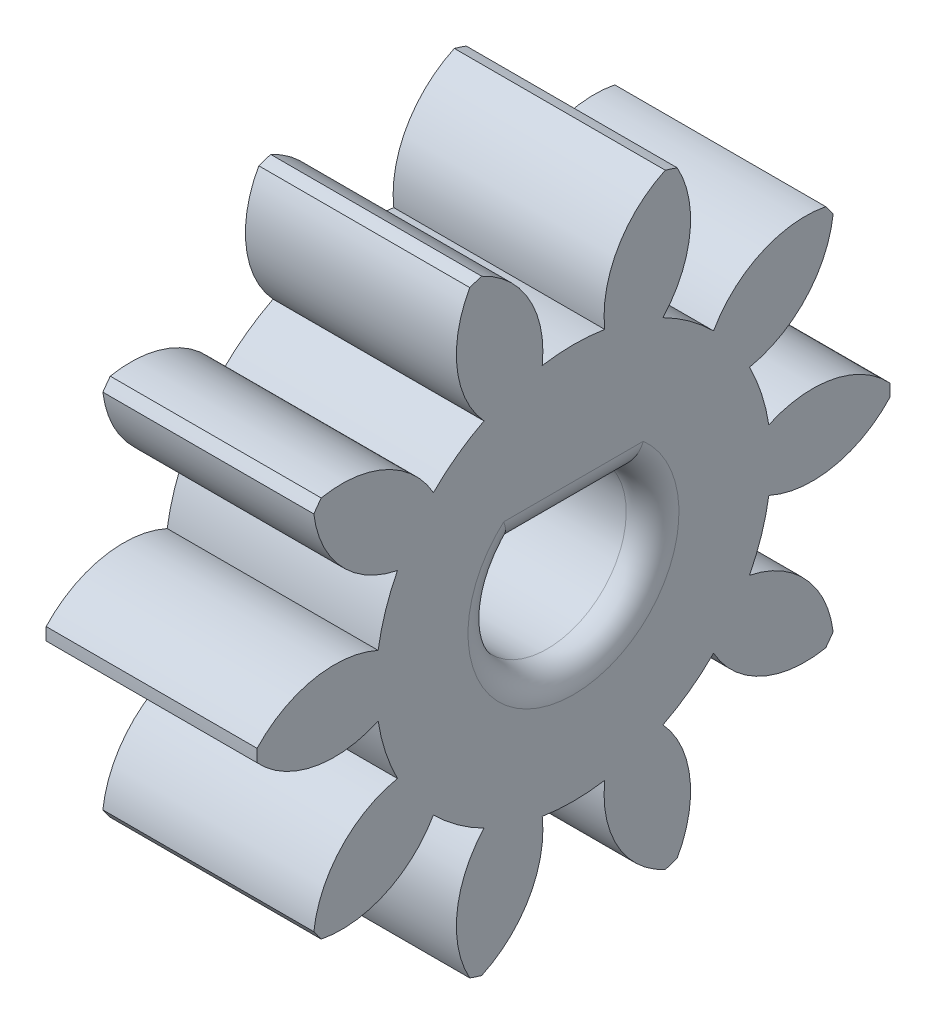
SolidWorks part; units mm, degrees
ref_plane "Plane1" through (0, 0, 0) normal (0, 0, 1) x (1, 0, 0)
ref_plane "Plane2" through (0, 0, 0) normal (0, 1, 0) x (1, 0, 0)
ref_plane "Plane3" through (0, 0, 0) normal (1, 0, 0) x (0, 0, -1)
sketch "HoldingSke" plane through (0, 0, 0) normal (0, 1, 0) x (1, 0, 0)
  line L0 (0, 0) -> (0.9848, -0.1736)
  line L1 (-15, 0) -> (100, 0) construction
  line L2 (0, 0) -> (-2.1039, 2.3779)
  line L3 (0, 0) -> (-11.863, 4.5341)
  line L4 (0, 0) -> (8.5048, 1.4996)
  line L5 (0, 0) -> (-46.8476, -17.4728)
  line L6 (0, 0) -> (-3.3159, -2.2372)
  line L7 (-2.1039, 2.3779) -> (8.6586, 51.2059)
  line L8 (-76.2, 54.61) -> (-75.3, 54.61)
  line L9 (-71.009, 38.7566) -> (-53.1078, 45.2721)
  line L10 (-76.2, 71.12) -> (104.1128, 71.12)
  line L11 (0, 0) -> (-4, 0)
  line L12 (-76.2, 101.6) -> (-76.162, 101.6)
  line L13 (24.9733, 27.94) -> (52.9518, 28.4284)
  line L14 (24.9733, 27.94) -> (24.9743, 27.94)
  line L15 (24.9733, 27.94) -> (100.4006, 29.5858)
  line L16 (-63.627, -1) -> (-12.827, -1)
  circle A0 centre (0, 0) radius 2.5
  circle A1 centre (0, 0) radius 3.749
  circle A2 centre (0, 0) radius 37.5
  circle A3 centre (0, 0) radius 2.5
  dimension "MHD" = 7.498
  dimension "Hub_dia" = 75
  dimension "Bore" = 5
  dimension "MBD" = 5
  dimension "Num_teeth" = 10
  dimension "Pitch" = 1
  dimension "Overall_len" = 50
  dimension "Show_teeth" = 10
  dimension "Thickness" = 4
  dimension "OAL" = 50.0001
  dimension "T_dim" = 0.9
  dimension "Ap" = 20
  dimension "H" = 19.05
  dimension "Pitch_radius" = 180.3128
  dimension "Width" = 4
  dimension "Backlash" = 0.038
  dimension "Addendum_fac" = 1
  dimension "Dedendum_fac" = 1.25
  dimension "Clearance_fac" = 0.25
  dimension "Dedendum_add" = 0.001
  dimension "Module" = 1
sketch "BasProSke" plane through (0, 0, 0) normal (0, 1, 0) x (1, 0, 0)
  line L0 (-10, 0) -> (60, 0) construction
  line L1 (0, 0) -> (0, 6)
  line L2 (0, 0) -> (4, 0)
  line L3 (4, 0) -> (4, 6)
  line L4 (4, 6) -> (0, 6)
  dimension "Thickness" = 4
  dimension "Diameter" = 12
revolve "Base-Revolve" add sketch "BasProSke" angle 360 about L0
sketch "TooCutSke" plane through (0, 0, 0) normal (1, 0, 0) x (0, 0, -1)
  line L1 (0, 0) -> (0, 107) construction
  line L2 (0, 0) -> (-0.8485, 4.9275) construction
  line L3 (0, 0) -> (-3.0584, 9.4126) construction
  line L4 (-0.8485, 4.9275) -> (-1.5292, 4.7063) construction
  arc A0 (0.5928, 3.7018) -> (-0.5928, 3.7018) centre (0, 0) ccw
  arc A1 (1.7758, 5.7578) -> (-1.7758, 5.7578) centre (0, 0) ccw
  circle A2 centre (0, 0) radius 5 construction
  circle A3 centre (0, 0) radius 4.6985 construction
  arc A4 (-0.5928, 3.7018) -> (-1.7758, 5.7578) centre (-2.5801, 3.9267) ccw
  arc A5 (1.7758, 5.7578) -> (0.5928, 3.7018) centre (2.5801, 3.9267) ccw
  dimension "Root_dia" = 7.498
  dimension "Overcut_dia" = 12.0508
  dimension "Pitch_dia" = 10
  dimension "Base_dia" = 9.3969
  dimension "Flank_rad" = 2
  dimension "Half_ang" = 18
  dimension "Half_CT" = 0.7157
extrude "ToothCut" cut sketch "TooCutSke" along normal through all
fillet "Breaks" [suppressed] radius 0.02
fillet "RootFillets" [suppressed] radius 0.251
pattern_circular "TeethCuts" count 10 every 36 about axis through (-10, 0, 0) along (1, 0, 0) of "ToothCut", "RootFillets", "Breaks"
sketch "HubNeaOneSke" plane through (0, 0, 0) normal (-1, 0, 0) x (0, 0, 1)
  circle A0 centre (0, 0) radius 3.749
  dimension "Diameter" = 7.498
extrude "HubNearOne" [suppressed] add sketch "HubNeaOneSke" along normal blind 46.0001
sketch "HubNeaBotSke" plane through (0, 0, 0) normal (-1, 0, 0) x (0, 0, 1)
  circle A0 centre (0, 0) radius 3.749
  dimension "Diameter" = 7.498
extrude "HubNearBoth" [suppressed] add sketch "HubNeaBotSke" along normal blind 23
ref_plane "FarPln" through (4, 0, 0) normal (1, 0, 0) x (0, 0, -1)
sketch "HubFarSke" plane through (4, 0, 0) normal (1, 0, 0) x (0, 0, -1)
  circle A0 centre (0, 0) radius 3.749
  dimension "Diameter" = 7.498
extrude "HubFar" [suppressed] add sketch "HubFarSke" along normal blind 23
sketch "BorSke" plane through (0, 0, 0) normal (1, 0, 0) x (0, 0, -1)
  circle A0 centre (0, 0) radius 2.5
  dimension "Diameter" = 5
extrude "Bore" cut sketch "BorSke" along normal mid plane 100.0001
sketch "KeySke" plane through (0, 0, 0) normal (1, 0, 0) x (0, 0, -1)
  line L0 (-1, 0) -> (-1, 3.4)
  line L1 (-1, 3.4) -> (1, 3.4)
  line L2 (1, 3.4) -> (1, 0)
  line L3 (0, 0) -> (0, 34) construction
  line L4 (-1, 0) -> (1, 0)
  dimension "Offset" = 3.4
  dimension "Width" = 2
extrude "Keyway" [suppressed] cut sketch "KeySke" along normal mid plane 100.0001
pattern_circular "Keyway2" [suppressed] count 2 every 90 about axis through (-10, 0, 0) along (1, 0, 0)
sketch "Sketch1" plane through (4, 0, 0) normal (1, 0, 0) x (0, 0, -1)
  line L0 (-1.118, 1) -> (1.118, 1)
  arc A0 (-1.118, 1) -> (1.118, 1) centre (0, 0) ccw
  circle A1 centre (0, 0) radius 2.5 construction
  circle A2 centre (0, 0) radius 2.5
  dimension "D1" = 1.5
  dimension "D2" = 1
extrude "Boss-Extrude1" add sketch "Sketch1" against normal up to surface (4 mm away) up to face at (0, 0, -2.5)
fillet "Fillet1" radius 0.5 4 edges at (0, 1, 0) (4, 1, 0) (0, -1.5, 0) (4, -1.5, 0)
equation "' \"Module@HoldingSke\" = 6.35"
equation "' \"Num_teeth@HoldingSke\" = 12"
equation "' \"Ap@HoldingSke\" =  20"
equation "' \"Ap@HoldingSke\" = 20"
equation "' \"Width@HoldingSke\" = 0.5 * 25.4"
equation "' \"Hub_dia@HoldingSke\"= 1 * 25.4"
equation "' \"Hub_dia@HoldingSke\" = 1 * 25.4"
equation "' \"Overall_len@HoldingSke\" = 1.0 * 25.4"
equation "' \"Bore@HoldingSke\" = 0.75 * 25.4"
equation "' \"T_dim@HoldingSke\" = 0.1 * 25.4"
equation "' \"Width@KeySke\" = 0.25 * 25.4"
equation "' \"Show_teeth@HoldingSke\" = 13"
equation "' \"Backlash@HoldingSke\" = 0.009 * 25.4"
equation "' \"Addendum_fac@HoldingSke\" = 1.0"
equation "' \"Dedendum_fac@HoldingSke\" = 1.25"
equation "' \"Dedendum_add@HoldingSke\" = 0.00005 * 25.4"
equation "' \"Clearance_fac@HoldingSke\" = 0.25"
equation "\"Pitch@HoldingSke\" = 1 / \"Module@HoldingSke\""
equation "\"Overcut_dia@TooCutSke\" = (\"Num_teeth@HoldingSke\" + 2 * \"Addendum_fac@HoldingSke\") / \"Pitch@HoldingSke\" + 0.002 * 25.4"
equation "\"Pitch_dia@TooCutSke\" = \"Num_teeth@HoldingSke\" / \"Pitch@HoldingSke\""
equation "\"Base_dia@TooCutSke\" = \"Num_teeth@HoldingSke\" / \"Pitch@HoldingSke\" * cos((\"Ap@HoldingSke\"  * 3.14159265 / 180))"
equation "\"Root_dia@TooCutSke\" = (\"Num_teeth@HoldingSke\" + 2) / \"Pitch@HoldingSke\" - 2 * (\"Addendum_fac@HoldingSke\" + \"Dedendum_fac@HoldingSke\") / \"Pitch@HoldingSke\" - \"Dedendum_add@HoldingSke\" * 2"
equation "\"Half_ang@TooCutSke\" = 180 / \"Num_teeth@HoldingSke\""
equation "\"Half_CT@TooCutSke\" = \"Num_teeth@HoldingSke\" / \"Pitch@HoldingSke\" * sin((3.14159265 / 2 / \"Num_teeth@HoldingSke\")) / 2 - 7 * \"Backlash@HoldingSke\" / 4"
equation "\"Flank_rad@TooCutSke\" = \"Num_teeth@HoldingSke\" / \"Pitch@HoldingSke\" / 5"
equation "\"Radius@RootFillets\" = \"Clearance_fac@HoldingSke\" / \"Pitch@HoldingSke\" + \"Dedendum_add@HoldingSke\""
equation "\"Break_rad@Breaks\" = 0.02 / \"Pitch@HoldingSke\""
equation "\"Thickness@HoldingSke\" = \"Width@HoldingSke\""
equation "\"OAL@HoldingSke\" = \"Thickness@HoldingSke\""
equation "\"MHD@HoldingSke\" = (\"Num_teeth@HoldingSke\" + 2) / \"Pitch@HoldingSke\" - 2 * (\"Addendum_fac@HoldingSke\" + \"Dedendum_fac@HoldingSke\")  / \"Pitch@HoldingSke\" - \"Dedendum_add@HoldingSke\" * 2"
equation "\"MBD@HoldingSke\" = (\"Num_teeth@HoldingSke\" + 2) / \"Pitch@HoldingSke\" - 2 * (\"Addendum_fac@HoldingSke\" + \"Dedendum_fac@HoldingSke\")  / \"Pitch@HoldingSke\" - \"Dedendum_add@HoldingSke\" * 2 - 0.002 * 25.4"
equation "\"MHD@HoldingSke\" = ((sgn( \"MHD@HoldingSke\" - \"Hub_dia@HoldingSke\" )-1)*( \"MHD@HoldingSke\" - \"Hub_dia@HoldingSke\" ))/-2+ \"Hub_dia@HoldingSke\""
equation "\"MBD@HoldingSke\" = ((sgn( \"MBD@HoldingSke\" - \"Bore@HoldingSke\" )-1)*( \"MBD@HoldingSke\" - \"Bore@HoldingSke\" ))/-2+ \"Bore@HoldingSke\""
equation "\"OAL@HoldingSke\" = ((sgn( \"OAL@HoldingSke\" - \"Overall_len@HoldingSke\" )+1)*( \"OAL@HoldingSke\" - \"Overall_len@HoldingSke\" ))/2 + \"Overall_len@HoldingSke\" + 0.000002 * 25.4"
equation "\"Num_teeth@TeethCuts\" = int( \"Show_teeth@HoldingSke\" ) + 1"
equation "\"Num_teeth@TeethCuts\" = ((sgn( \"Num_teeth@TeethCuts\" - \"Num_teeth@HoldingSke\" )-1)*( \"Num_teeth@TeethCuts\" - \"Num_teeth@HoldingSke\" ))/-2+ \"Num_teeth@HoldingSke\""
equation "\"Num_teeth@TeethCuts\" = ((sgn( \"Num_teeth@TeethCuts\" - 2.0)+1)*( \"Num_teeth@TeethCuts\" - 2.0))/2 +2.0"
equation "\"Angle@TeethCuts\" = 360.0 / \"Num_teeth@HoldingSke\""
equation "\"Diameter@BasProSke\" = (\"Num_teeth@HoldingSke\" + 2 * \"Addendum_fac@HoldingSke\") / \"Pitch@HoldingSke\""
equation "\"Thickness@BasProSke\"  = \"Thickness@HoldingSke\""
equation "' \"Fillet_rad@BasProSke\" =  \"Thickness@HoldingSke\" * 0.05"
equation "' \"Fillet_rad@BasProSke\" = \"Thickness@HoldingSke\" * 0.05"
equation "\"MHD@HoldingSke\" = ((sgn( \"MHD@HoldingSke\" - \"Root_dia@TooCutSke\" )-1)*( \"MHD@HoldingSke\" - \"Root_dia@TooCutSke\" ))/-2+ \"Root_dia@TooCutSke\""
equation "\"Diameter@HubNeaOneSke\" = \"MHD@HoldingSke\""
equation "\"Length@HubNearOne\" = \"OAL@HoldingSke\" - \"Thickness@BasProSke\""
equation "\"Diameter@HubNeaBotSke\" = \"MHD@HoldingSke\""
equation "\"Length@HubNearBoth\" = ( \"OAL@HoldingSke\" - \"Thickness@BasProSke\" ) / 2.0"
equation "\"Thickness@FarPln\" = \"Thickness@BasProSke\""
equation "\"Diameter@HubFarSke\" = \"MHD@HoldingSke\""
equation "\"Length@HubFar\" = ( \"OAL@HoldingSke\" - \"Thickness@BasProSke\" ) / 2.0"
equation "\"Diameter@BorSke\" = \"MBD@HoldingSke\""
equation "\"D1@Bore\" = \"OAL@HoldingSke\" * 2.0"
equation "\"D1@Keyway\" = \"OAL@HoldingSke\" * 2.0"
equation "\"Offset@KeySke\" = \"T_dim@HoldingSke\" + \"MBD@HoldingSke\" / 2.0"
